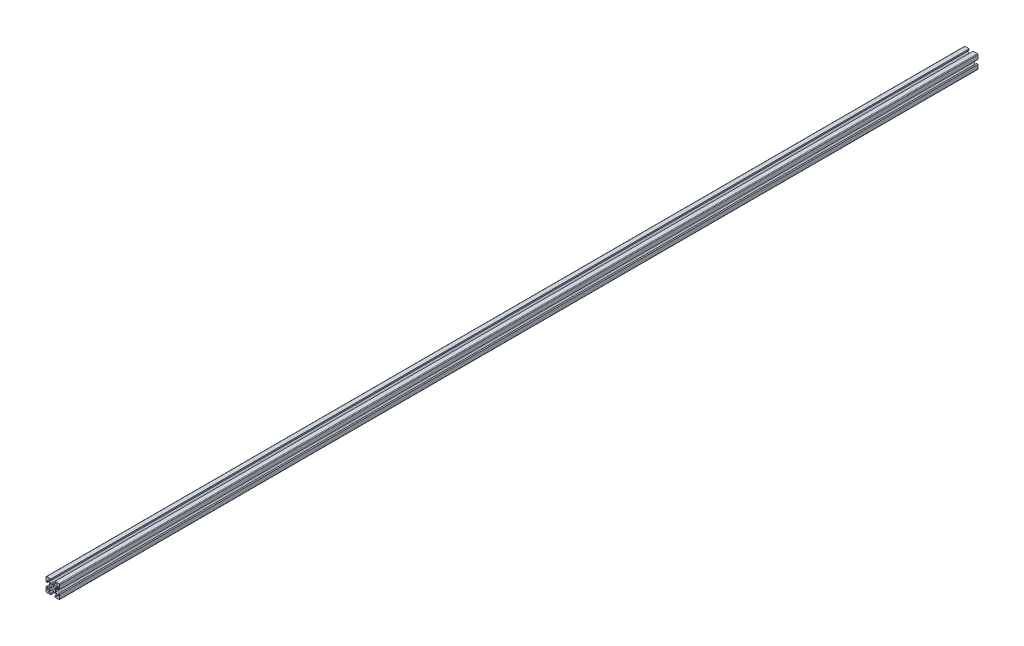
SolidWorks part; units mm, degrees
ref_plane "Front Plane" through (0, 0, 0) normal (0, 0, 1) x (1, 0, 0)
ref_plane "Top Plane" through (0, 0, 0) normal (0, 1, 0) x (1, 0, 0)
ref_plane "Right Plane" through (0, 0, 0) normal (1, 0, 0) x (0, 0, -1)
ref_plane "Plane1" through (0, 0, -2000) normal (0, 0, -1) x (-1, 0, 0)
sketch "Sketch1" plane through (0, 0, -2000) normal (0, 0, -1) x (-1, 0, 0)
  line L0 (10, -3) -> (8, -3)
  line L1 (8, -3) -> (8, -6)
  line L2 (8, -6) -> (7.0607, -6)
  line L3 (7.0607, -6) -> (4, -2.9393)
  line L4 (4, -2.9393) -> (4, -2.5)
  line L5 (4, -2.5) -> (3.751, -1.2189)
  line L6 (3.751, -1.2189) -> (3.933, -0.9036)
  line L7 (3.933, -0.4036) -> (3.7, 0)
  line L8 (3.7, 0) -> (3.933, 0.4036)
  line L9 (4, 0.6536) -> (4, 2.9393)
  line L10 (4, 2.9393) -> (7.0607, 6)
  line L11 (7.0607, 6) -> (8, 6)
  line L12 (8, 6) -> (8, 3)
  line L13 (8, 3) -> (10, 3)
  line L14 (10, 3) -> (10, 9)
  line L15 (9, 10) -> (3, 10)
  line L16 (3, 10) -> (3, 8)
  line L17 (3, 8) -> (6, 8)
  line L18 (6, 8) -> (6, 7.0607)
  line L19 (6, 7.0607) -> (2.9393, 4)
  line L20 (2.9393, 4) -> (2.5, 4)
  line L21 (2.5, 4) -> (1.2189, 3.751)
  line L22 (1.2189, 3.751) -> (0.9036, 3.933)
  line L23 (0.4036, 3.933) -> (0, 3.7)
  line L24 (0, 3.7) -> (-0.4036, 3.933)
  line L25 (-0.6536, 4) -> (-2.9393, 4)
  line L26 (-2.9393, 4) -> (-6, 7.0607)
  line L27 (-6, 7.0607) -> (-6, 8)
  line L28 (-6, 8) -> (-3, 8)
  line L29 (-3, 8) -> (-3, 10)
  line L30 (-3, 10) -> (-9, 10)
  line L31 (-10, 9) -> (-10, 3)
  line L32 (-10, 3) -> (-8, 3)
  line L33 (-8, 3) -> (-8, 6)
  line L34 (-8, 6) -> (-7.0607, 6)
  line L35 (-7.0607, 6) -> (-4, 2.9393)
  line L36 (-4, 2.9393) -> (-4, 2.5)
  line L37 (-4, 2.5) -> (-3.751, 1.2189)
  line L38 (-3.751, 1.2189) -> (-3.933, 0.9036)
  line L39 (-3.933, 0.4036) -> (-3.7, 0)
  line L40 (-3.7, 0) -> (-3.933, -0.4036)
  line L41 (-4, -0.6536) -> (-4, -2.9393)
  line L42 (-4, -2.9393) -> (-7.0607, -6)
  line L43 (-7.0607, -6) -> (-8, -6)
  line L44 (-8, -6) -> (-8, -3)
  line L45 (-8, -3) -> (-10, -3)
  line L46 (-10, -3) -> (-10, -9)
  line L47 (-9, -10) -> (-3, -10)
  line L48 (-3, -10) -> (-3, -8)
  line L49 (-3, -8) -> (-6, -8)
  line L50 (-6, -8) -> (-6, -7.0607)
  line L51 (-6, -7.0607) -> (-2.9393, -4)
  line L52 (-2.9393, -4) -> (-2.5, -4)
  line L53 (-2.5, -4) -> (-1.2189, -3.751)
  line L54 (-1.2189, -3.751) -> (-0.9036, -3.933)
  line L55 (-0.4036, -3.933) -> (0, -3.7)
  line L56 (0, -3.7) -> (0.4036, -3.933)
  line L57 (0.6536, -4) -> (2.9393, -4)
  line L58 (2.9393, -4) -> (6, -7.0607)
  line L59 (6, -7.0607) -> (6, -8)
  line L60 (6, -8) -> (3, -8)
  line L61 (3, -8) -> (3, -10)
  line L62 (3, -10) -> (9, -10)
  line L63 (10, -9) -> (10, -3)
  circle A0 centre (0, 0) radius 2.1
  arc A1 (3.933, -0.9036) -> (3.933, -0.4036) centre (3.5, -0.6536) ccw
  arc A2 (3.933, 0.4036) -> (4, 0.6536) centre (3.5, 0.6536) ccw
  arc A3 (10, 9) -> (9, 10) centre (9, 9) ccw
  arc A4 (0.9036, 3.933) -> (0.4036, 3.933) centre (0.6536, 3.5) ccw
  arc A5 (-0.4036, 3.933) -> (-0.6536, 4) centre (-0.6536, 3.5) ccw
  arc A6 (-9, 10) -> (-10, 9) centre (-9, 9) ccw
  arc A7 (-3.933, 0.9036) -> (-3.933, 0.4036) centre (-3.5, 0.6536) ccw
  arc A8 (-3.933, -0.4036) -> (-4, -0.6536) centre (-3.5, -0.6536) ccw
  arc A9 (-10, -9) -> (-9, -10) centre (-9, -9) ccw
  arc A10 (-0.9036, -3.933) -> (-0.4036, -3.933) centre (-0.6536, -3.5) ccw
  arc A11 (0.4036, -3.933) -> (0.6536, -4) centre (0.6536, -3.5) ccw
  arc A12 (9, -10) -> (10, -9) centre (9, -9) ccw
extrude "Boss-Extrude1" add sketch "Sketch1" against normal blind 1340
equation "\"D1@Boss-Extrude1\"=420*3+20*4"
